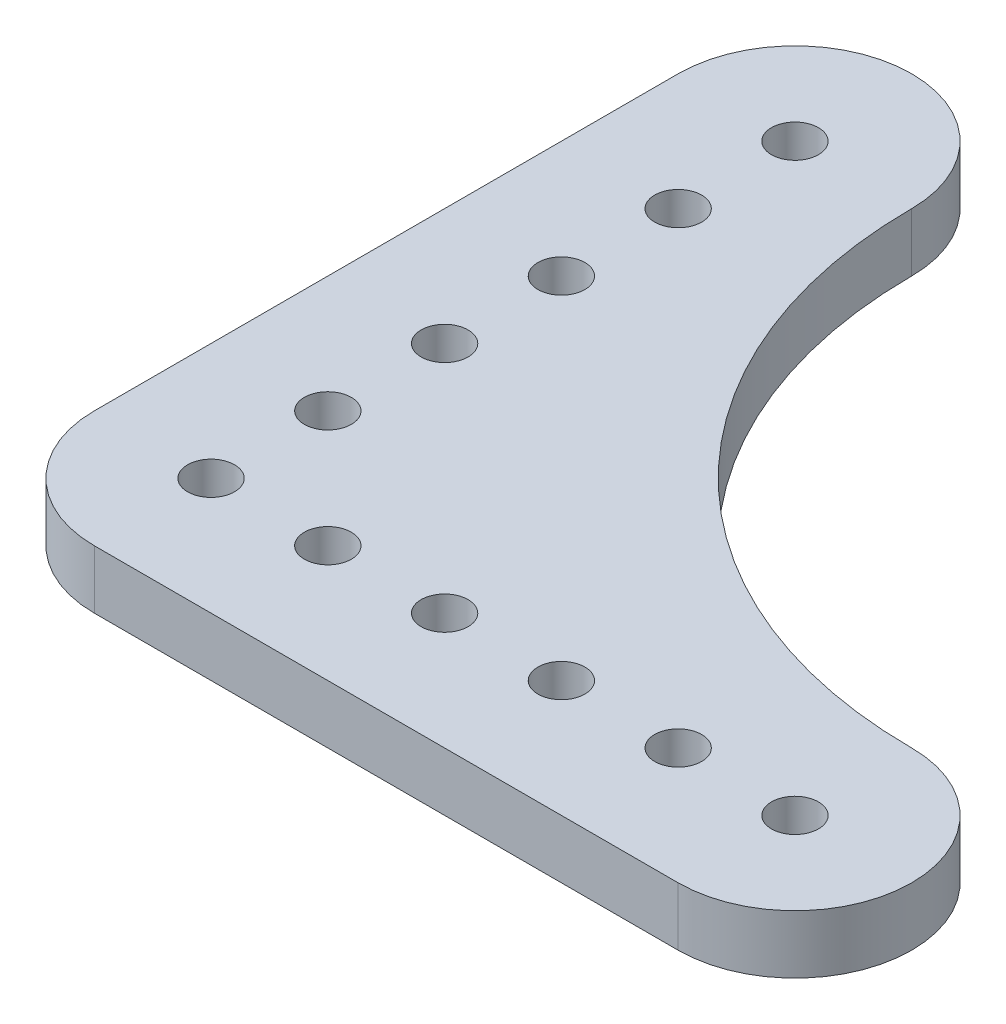
SolidWorks part; units mm, degrees
material "Birch Plywood"
ref_plane "Front Plane" through (0, 0, 0) normal (0, 0, 1) x (1, 0, 0)
ref_plane "Top Plane" through (0, 0, 0) normal (0, 1, 0) x (1, 0, 0)
ref_plane "Right Plane" through (0, 0, 0) normal (1, 0, 0) x (0, 0, -1)
sketch "Sketch1" plane through (0, 0, 0) normal (0, 1, 0) x (1, 0, 0)
  line L0 (0, 12.7) -> (0, 0) construction
  line L1 (0, 0) -> (12.7, 0) construction
  line L2 (63.5, 0) -> (0, 0) construction
  line L3 (63.5, -12.7) -> (0, -12.7)
  line L4 (63.5, 12.7) -> (0, 12.7)
  line L5 (0, 0) -> (0, 63.5) construction
  line L6 (-12.7, 0) -> (-12.7, 63.5)
  line L7 (12.7, 0) -> (12.7, 63.5)
  circle A0 centre (0, 0) radius 2.5527
  circle A1 centre (12.7, 0) radius 2.5527
  circle A2 centre (25.4, 0) radius 2.5527
  circle A3 centre (38.1, 0) radius 2.5527
  circle A4 centre (50.8, 0) radius 2.5527
  circle A5 centre (63.5, 0) radius 2.5527
  circle A6 centre (0, 12.7) radius 2.5527
  circle A7 centre (0, 25.4) radius 2.5527
  circle A8 centre (0, 38.1) radius 2.5527
  circle A9 centre (0, 50.8) radius 2.5527
  circle A10 centre (0, 63.5) radius 2.5527
  arc A11 (63.5, -12.7) -> (63.5, 12.7) centre (63.5, 0) ccw
  arc A12 (0, 12.7) -> (0, -12.7) centre (0, 0) ccw
  arc A13 (-12.7, 0) -> (12.7, 0) centre (0, 0) ccw
  arc A14 (12.7, 63.5) -> (-12.7, 63.5) centre (0, 63.5) ccw
  arc A15 (12.7, 63.5) -> (63.5, 12.7) centre (63.5, 63.5) ccw
  point P14 (31.75, 0)
  point P28 (0, 31.75)
  dimension "D1" = 5.1054
  dimension "D6" = 12.7
  dimension "D3" = 12.7
  dimension "D4" = 12.7
  dimension "D2" = 6
  dimension "D5" = 6
extrude "Boss-Extrude1" add sketch "Sketch1" along normal mid plane 6.35 contours L7 A14 L6 A12 A6 L4 A7 A8 A9 A10 | A15 L7 L4 | A13 L3 A11 L4 L7 A1 A2 A3 A4 A5 | A12 A13 A1 L7 L4 A6 A0
